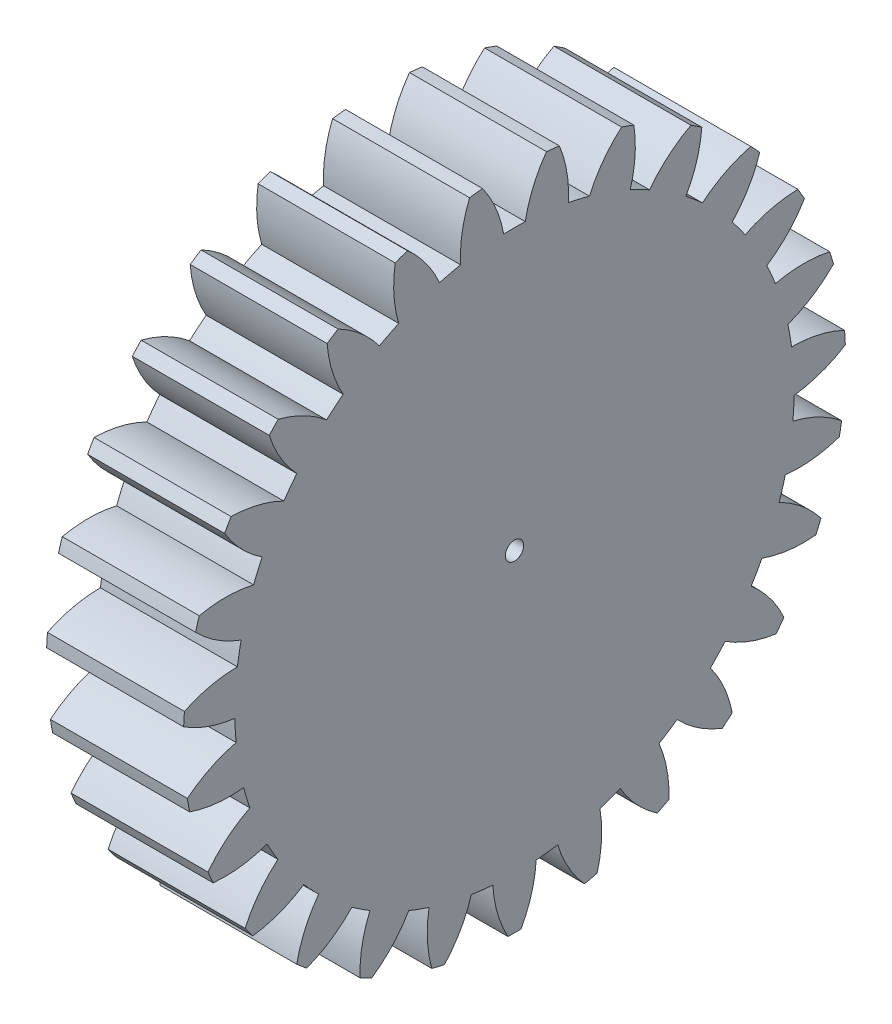
SolidWorks part; units mm, degrees
ref_plane "Plane1" through (0, 0, 0) normal (0, 0, 1) x (1, 0, 0)
ref_plane "Plane2" through (0, 0, 0) normal (0, 1, 0) x (1, 0, 0)
ref_plane "Plane3" through (0, 0, 0) normal (1, 0, 0) x (0, 0, -1)
sketch "HoldingSke" plane through (0, 0, 0) normal (0, 1, 0) x (1, 0, 0)
  line L0 (0, 0) -> (0.891, -0.454)
  line L1 (-15, 0) -> (100, 0) construction
  line L2 (0, 0) -> (-2.1039, 2.3779)
  line L3 (0, 0) -> (-11.863, 4.5341)
  line L4 (0, 0) -> (7.6947, 3.9207)
  line L5 (0, 0) -> (-46.8476, -17.4728)
  line L6 (0, 0) -> (-4.9738, -3.3558)
  line L7 (-2.1039, 2.3779) -> (8.6586, 51.2059)
  line L8 (-76.2, 54.61) -> (-76.1, 54.61)
  line L9 (-71.009, 38.7566) -> (-53.1078, 45.2721)
  line L10 (-76.2, 71.12) -> (104.1128, 71.12)
  line L11 (0, 0) -> (-6, 0)
  line L12 (-76.2, 101.6) -> (-76.162, 101.6)
  line L13 (24.9733, 27.94) -> (52.9518, 28.4284)
  line L14 (24.9733, 27.94) -> (24.9743, 27.94)
  line L15 (24.9733, 27.94) -> (100.4006, 29.5858)
  line L16 (-63.627, -1) -> (-12.827, -1)
  circle A0 centre (0, 0) radius 0.4
  circle A1 centre (0, 0) radius 12.249
  circle A2 centre (0, 0) radius 37.5
  circle A3 centre (0, 0) radius 0.4
  dimension "MHD" = 24.498
  dimension "Hub_dia" = 75
  dimension "Bore" = 0.8
  dimension "MBD" = 0.8
  dimension "Num_teeth" = 27
  dimension "Pitch_radius" = 180.3128
  dimension "Pitch" = 1
  dimension "Width" = 6
  dimension "Overall_len" = 50
  dimension "Show_teeth" = 27
  dimension "Thickness" = 6
  dimension "OAL" = 50.0001
  dimension "T_dim" = 0.1
  dimension "Ap" = 20
  dimension "H" = 19.05
  dimension "Backlash" = 0.038
  dimension "Addendum_fac" = 1
  dimension "Dedendum_fac" = 1.25
  dimension "Clearance_fac" = 0.25
  dimension "Dedendum_add" = 0.001
  dimension "Module" = 1
sketch "BasProSke" plane through (0, 0, 0) normal (0, 1, 0) x (1, 0, 0)
  line L0 (-10, 0) -> (60, 0) construction
  line L1 (0, 0) -> (0, 14.5)
  line L2 (0, 0) -> (6, 0)
  line L3 (6, 0) -> (6, 14.5)
  line L4 (6, 14.5) -> (0, 14.5)
  dimension "Diameter" = 29
  dimension "Thickness" = 6
revolve "Base-Revolve" add sketch "BasProSke" angle 360 about L0
sketch "TooCutSke" plane through (0, 0, 0) normal (1, 0, 0) x (0, 0, -1)
  line L1 (0, 0) -> (0, 107) construction
  line L2 (0, 0) -> (-0.8514, 13.4731) construction
  line L3 (0, 0) -> (-3.1301, 26.7794) construction
  line L4 (-0.8514, 13.4731) -> (-1.565, 13.3897) construction
  arc A0 (0.4741, 12.2398) -> (-0.4741, 12.2398) centre (0, 0) ccw
  arc A1 (1.4167, 14.4561) -> (-1.4167, 14.4561) centre (0, 0) ccw
  circle A2 centre (0, 0) radius 13.5 construction
  circle A3 centre (0, 0) radius 12.6859 construction
  arc A4 (-0.4741, 12.2398) -> (-1.4167, 14.4561) centre (-5.7895, 11.2877) ccw
  arc A5 (1.4167, 14.4561) -> (0.4741, 12.2398) centre (5.7895, 11.2877) ccw
  dimension "Root_dia" = 24.498
  dimension "Overcut_dia" = 29.0508
  dimension "Pitch_dia" = 27
  dimension "Base_dia" = 25.3717
  dimension "Flank_rad" = 5.4
  dimension "Half_ang" = 6.667
  dimension "Half_CT" = 0.7185
extrude "ToothCut" cut sketch "TooCutSke" along normal through all
fillet "Breaks" [suppressed] radius 0.02
fillet "RootFillets" [suppressed] radius 0.251
pattern_circular "TeethCuts" count 27 every 13.333 about axis through (-10, 0, 0) along (1, 0, 0) of "ToothCut", "RootFillets", "Breaks"
sketch "HubNeaOneSke" plane through (0, 0, 0) normal (-1, 0, 0) x (0, 0, 1)
  circle A0 centre (0, 0) radius 12.249
  dimension "Diameter" = 24.498
extrude "HubNearOne" [suppressed] add sketch "HubNeaOneSke" along normal blind 44.0001
sketch "HubNeaBotSke" plane through (0, 0, 0) normal (-1, 0, 0) x (0, 0, 1)
  circle A0 centre (0, 0) radius 12.249
  dimension "Diameter" = 24.498
extrude "HubNearBoth" [suppressed] add sketch "HubNeaBotSke" along normal blind 22
ref_plane "FarPln" through (6, 0, 0) normal (1, 0, 0) x (0, 0, -1)
sketch "HubFarSke" plane through (6, 0, 0) normal (1, 0, 0) x (0, 0, -1)
  circle A0 centre (0, 0) radius 12.249
  dimension "Diameter" = 24.498
extrude "HubFar" [suppressed] add sketch "HubFarSke" along normal blind 22
sketch "BorSke" plane through (0, 0, 0) normal (1, 0, 0) x (0, 0, -1)
  circle A0 centre (0, 0) radius 0.4
  dimension "Diameter" = 0.8
extrude "Bore" cut sketch "BorSke" along normal mid plane 100.0001
sketch "KeySke" plane through (0, 0, 0) normal (1, 0, 0) x (0, 0, -1)
  line L0 (-0.05, 0) -> (-0.05, 0.5)
  line L1 (-0.05, 0.5) -> (0.05, 0.5)
  line L2 (0.05, 0.5) -> (0.05, 0)
  line L3 (0, 0) -> (0, 34) construction
  line L4 (-0.05, 0) -> (0.05, 0)
  dimension "Offset" = 0.5
  dimension "Width" = 0.1
extrude "Keyway" [suppressed] cut sketch "KeySke" along normal mid plane 100.0001
pattern_circular "Keyway2" [suppressed] count 2 every 90 about axis through (-10, 0, 0) along (1, 0, 0)
sketch "Sketch1" plane through (6, 0, 0) normal (1, 0, 0) x (0, 0, -1)
  line L1 (5, 5) -> (-5, 5)
  line L2 (-5, 5) -> (-5, -5)
  line L3 (-5, -5) -> (5, -5)
  line L4 (5, -5) -> (5, 5)
  circle A0 centre (0, 0) radius 5 construction
  dimension "D1" = 10
equation "' \"Module@HoldingSke\" = 6.35"
equation "' \"Num_teeth@HoldingSke\" = 12"
equation "' \"Ap@HoldingSke\" =  20"
equation "' \"Width@HoldingSke\" = 0.5 * 25.4"
equation "' \"Hub_dia@HoldingSke\"= 1 * 25.4"
equation "' \"Overall_len@HoldingSke\" = 1.0 * 25.4"
equation "' \"Bore@HoldingSke\" = 0.75 * 25.4"
equation "' \"T_dim@HoldingSke\" = 0.1 * 25.4"
equation "' \"Width@KeySke\" = 0.25 * 25.4"
equation "' \"Show_teeth@HoldingSke\" = 13"
equation "' \"Backlash@HoldingSke\" = 0.009 * 25.4"
equation "' \"Addendum_fac@HoldingSke\" = 1.0"
equation "' \"Dedendum_fac@HoldingSke\" = 1.25"
equation "' \"Dedendum_add@HoldingSke\" = 0.00005 * 25.4"
equation "' \"Clearance_fac@HoldingSke\" = 0.25"
equation "\"Pitch@HoldingSke\" = 1 / \"Module@HoldingSke\""
equation "\"Overcut_dia@TooCutSke\" = (\"Num_teeth@HoldingSke\" + 2 * \"Addendum_fac@HoldingSke\") / \"Pitch@HoldingSke\" + 0.002 * 25.4"
equation "\"Pitch_dia@TooCutSke\" = \"Num_teeth@HoldingSke\" / \"Pitch@HoldingSke\""
equation "\"Base_dia@TooCutSke\" = \"Num_teeth@HoldingSke\" / \"Pitch@HoldingSke\" * cos((\"Ap@HoldingSke\"  * 3.14159265 / 180))"
equation "\"Root_dia@TooCutSke\" = (\"Num_teeth@HoldingSke\" + 2) / \"Pitch@HoldingSke\" - 2 * (\"Addendum_fac@HoldingSke\" + \"Dedendum_fac@HoldingSke\") / \"Pitch@HoldingSke\" - \"Dedendum_add@HoldingSke\" * 2"
equation "\"Half_ang@TooCutSke\" = 180 / \"Num_teeth@HoldingSke\""
equation "\"Half_CT@TooCutSke\" = \"Num_teeth@HoldingSke\" / \"Pitch@HoldingSke\" * sin((3.14159265 / 2 / \"Num_teeth@HoldingSke\")) / 2 - 7 * \"Backlash@HoldingSke\" / 4"
equation "\"Flank_rad@TooCutSke\" = \"Num_teeth@HoldingSke\" / \"Pitch@HoldingSke\" / 5"
equation "\"Radius@RootFillets\" = \"Clearance_fac@HoldingSke\" / \"Pitch@HoldingSke\" + \"Dedendum_add@HoldingSke\""
equation "\"Break_rad@Breaks\" = 0.02 / \"Pitch@HoldingSke\""
equation "\"Thickness@HoldingSke\" = \"Width@HoldingSke\""
equation "\"OAL@HoldingSke\" = \"Thickness@HoldingSke\""
equation "\"MHD@HoldingSke\" = (\"Num_teeth@HoldingSke\" + 2) / \"Pitch@HoldingSke\" - 2 * (\"Addendum_fac@HoldingSke\" + \"Dedendum_fac@HoldingSke\")  / \"Pitch@HoldingSke\" - \"Dedendum_add@HoldingSke\" * 2"
equation "\"MBD@HoldingSke\" = (\"Num_teeth@HoldingSke\" + 2) / \"Pitch@HoldingSke\" - 2 * (\"Addendum_fac@HoldingSke\" + \"Dedendum_fac@HoldingSke\")  / \"Pitch@HoldingSke\" - \"Dedendum_add@HoldingSke\" * 2 - 0.002 * 25.4"
equation "\"MHD@HoldingSke\" = ((sgn( \"MHD@HoldingSke\" - \"Hub_dia@HoldingSke\" )-1)*( \"MHD@HoldingSke\" - \"Hub_dia@HoldingSke\" ))/-2+ \"Hub_dia@HoldingSke\""
equation "\"MBD@HoldingSke\" = ((sgn( \"MBD@HoldingSke\" - \"Bore@HoldingSke\" )-1)*( \"MBD@HoldingSke\" - \"Bore@HoldingSke\" ))/-2+ \"Bore@HoldingSke\""
equation "\"OAL@HoldingSke\" = ((sgn( \"OAL@HoldingSke\" - \"Overall_len@HoldingSke\" )+1)*( \"OAL@HoldingSke\" - \"Overall_len@HoldingSke\" ))/2 + \"Overall_len@HoldingSke\" + 0.000002 * 25.4"
equation "\"Num_teeth@TeethCuts\" = int( \"Show_teeth@HoldingSke\" ) + 1"
equation "\"Num_teeth@TeethCuts\" = ((sgn( \"Num_teeth@TeethCuts\" - \"Num_teeth@HoldingSke\" )-1)*( \"Num_teeth@TeethCuts\" - \"Num_teeth@HoldingSke\" ))/-2+ \"Num_teeth@HoldingSke\""
equation "\"Num_teeth@TeethCuts\" = ((sgn( \"Num_teeth@TeethCuts\" - 2.0)+1)*( \"Num_teeth@TeethCuts\" - 2.0))/2 +2.0"
equation "\"Angle@TeethCuts\" = 360.0 / \"Num_teeth@HoldingSke\""
equation "\"Diameter@BasProSke\" = (\"Num_teeth@HoldingSke\" + 2 * \"Addendum_fac@HoldingSke\") / \"Pitch@HoldingSke\""
equation "\"Thickness@BasProSke\"  = \"Thickness@HoldingSke\""
equation "' \"Fillet_rad@BasProSke\" =  \"Thickness@HoldingSke\" * 0.05"
equation "\"MHD@HoldingSke\" = ((sgn( \"MHD@HoldingSke\" - \"Root_dia@TooCutSke\" )-1)*( \"MHD@HoldingSke\" - \"Root_dia@TooCutSke\" ))/-2+ \"Root_dia@TooCutSke\""
equation "\"Diameter@HubNeaOneSke\" = \"MHD@HoldingSke\""
equation "\"Length@HubNearOne\" = \"OAL@HoldingSke\" - \"Thickness@BasProSke\""
equation "\"Diameter@HubNeaBotSke\" = \"MHD@HoldingSke\""
equation "\"Length@HubNearBoth\" = ( \"OAL@HoldingSke\" - \"Thickness@BasProSke\" ) / 2.0"
equation "\"Thickness@FarPln\" = \"Thickness@BasProSke\""
equation "\"Diameter@HubFarSke\" = \"MHD@HoldingSke\""
equation "\"Length@HubFar\" = ( \"OAL@HoldingSke\" - \"Thickness@BasProSke\" ) / 2.0"
equation "\"Diameter@BorSke\" = \"MBD@HoldingSke\""
equation "\"D1@Bore\" = \"OAL@HoldingSke\" * 2.0"
equation "\"D1@Keyway\" = \"OAL@HoldingSke\" * 2.0"
equation "\"Offset@KeySke\" = \"T_dim@HoldingSke\" + \"MBD@HoldingSke\" / 2.0"
